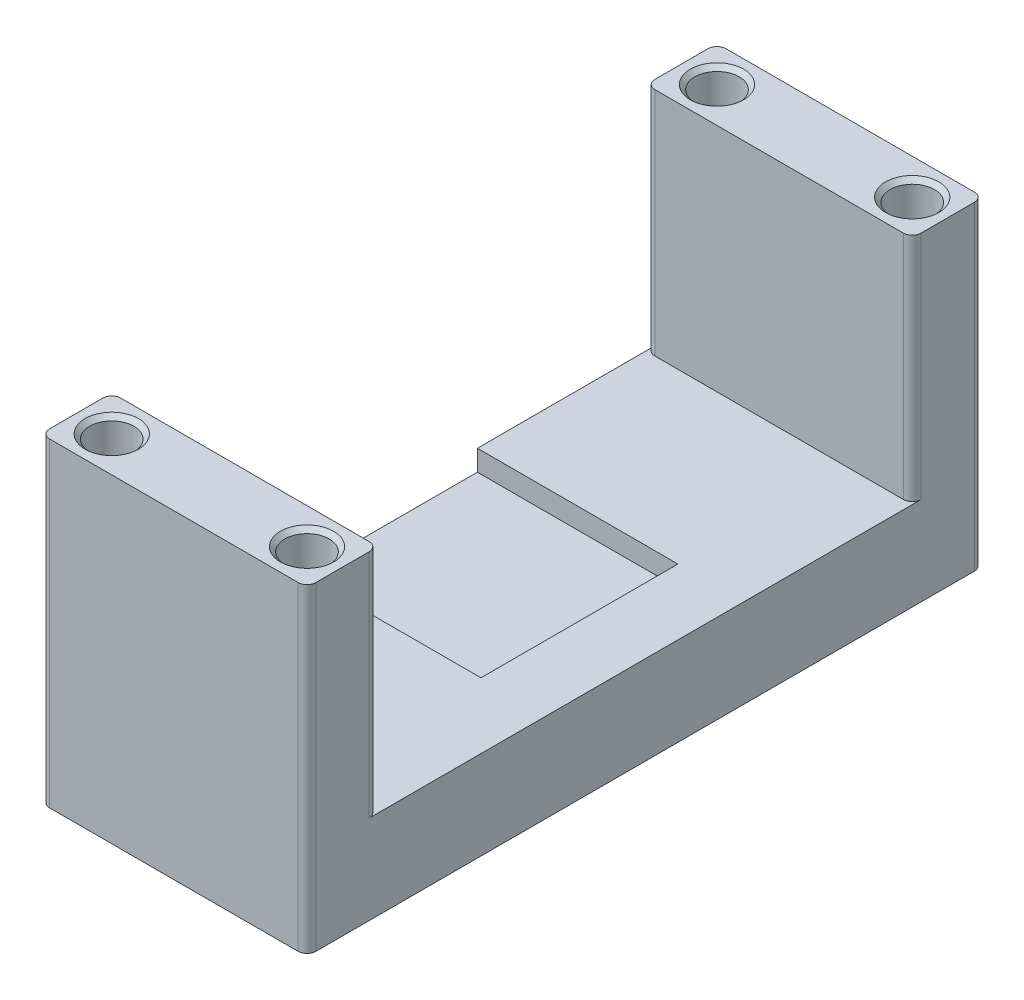
SolidWorks part; units mm, degrees
ref_plane "Front" through (0, 0, 0) normal (0, 0, 1) x (1, 0, 0)
ref_plane "Top" through (0, 0, 0) normal (0, 1, 0) x (1, 0, 0)
ref_plane "Right" through (0, 0, 0) normal (1, 0, 0) x (0, 0, -1)
sketch "Sketch1" plane through (0, 0, 0) normal (0, 1, 0) x (1, 0, 0)
  line L1 (-20.5, 11) -> (7.5, 11) construction
  line L2 (-20.5, 11) -> (-20.5, -11) construction
  line L3 (-20.5, -11) -> (7.5, -11) construction
  line L4 (7.5, 11) -> (7.5, -11) construction
  line L5 (-5.5, 9) -> (5.5, 9) construction
  line L6 (-5.5, 9) -> (-5.5, -9) construction
  line L7 (-5.5, -9) -> (5.5, -9) construction
  line L8 (5.5, 9) -> (5.5, -9) construction
  line L9 (-15, 38.1) -> (15, 38.1)
  line L10 (-15, 38.1) -> (-15, -38.1)
  line L11 (-15, -38.1) -> (15, -38.1)
  line L12 (15, 38.1) -> (15, -38.1)
  point P4 (5.5, 0)
  point P6 (7.5, 0)
  point P11 (0, 9)
  point P17 (0, -38.1)
  point P18 (15, 0)
  dimension "D1" = 22
  dimension "D2" = 28
  dimension "D3" = 7.5
  dimension "D4" = 18
  dimension "D5" = 11
  dimension "D6" = 76.2
  dimension "D7" = 30
extrude "Boss-Extrude1" add sketch "Sketch1" against normal blind 10
sketch "Sketch2" plane through (0, 0, 0) normal (0, 1, 0) x (1, 0, 0)
  line L0 (-15, 38.1) -> (-15, -38.1) construction
  line L1 (-15, 11.1) -> (7.6, 11.1)
  line L2 (-15, 11.1) -> (-15, -11.1)
  line L3 (-15, -11.1) -> (7.6, -11.1)
  line L4 (7.6, 11.1) -> (7.6, -11.1)
  line L5 (7.5, 11) -> (7.5, -11) construction
  point P6 (7.6, 0)
  dimension "D1" = 22.2
  dimension "D2" = 0.1
extrude "Cut-Extrude2" cut sketch "Sketch2" against normal blind 2.335
sketch "Sketch3" plane through (0, 0, 0) normal (0, 1, 0) x (1, 0, 0)
  line L0 (15, 38.1) -> (15, -38.1) construction
  line L1 (-15, 38.1) -> (15, 38.1)
  line L2 (-15, 38.1) -> (-15, 30.1)
  line L3 (-15, 30.1) -> (15, 30.1)
  line L4 (15, 38.1) -> (15, 30.1)
  line L6 (-15, -38.1) -> (15, -38.1)
  line L7 (-15, -38.1) -> (-15, -30.1)
  line L8 (-15, -30.1) -> (15, -30.1)
  line L9 (15, -38.1) -> (15, -30.1)
  dimension "D1" = 8
extrude "Boss-Extrude2" add sketch "Sketch3" along normal blind 26
hole_wizard "Ø5.0mm Dowel Hole1" positions "Sketch4" profile "Sketch6" hole size "Ø5.0" standard "ANSI Metric"
sketch "Sketch4" plane through (0, 26, 0) normal (0, 1, 0) x (1, 0, 0)
  line L0 (-15, 38.1) -> (-15, 30.1) construction
  line L2 (-15, -30.1) -> (-15, -38.1) construction
  line L3 (-15, 38.1) -> (-15, -38.1) construction
  line L4 (15, 38.1) -> (15, -38.1) construction
  point P0 (-11, 34.1)
  point P2 (11, 34.1)
  point P4 (11, -34.1)
  point P6 (-11, -34.1)
  point P12 (-15, 34.1)
  point P20 (-15, -34.1)
  dimension "D1" = 4
  dimension "D2" = 4
sketch "Sketch6" plane through (-11, 26, -34.1) normal (1, 0, 0) x (0, 0, 1)
  line L0 (0, 0) -> (0, 4.6)
  line L1 (0, 4.6) -> (2.5, 4.6)
  line L2 (2.5, 4.6) -> (2.5, 0.5)
  line L3 (2.5, 0.5) -> (3, 0)
  line L5 (3, 0) -> (0, 0)
  line L6 (-2.5, 0.5) -> (-3, 0) construction
  line L10 (0, 4.6) -> (-2.5, 4.6) construction
  line L11 (0, -6.35) -> (0, 107.95) construction
  dimension "Hole Dia." = 5
  dimension "Hole Depth" = 4.6
  dimension "Near C'Sink Dia." = 6
  dimension "Near C'Sink Angle" = 90
  dimension "Drill Angle" = 180
fillet "Fillet1" radius 1 8 edges at (15, 8, -38.1) (15, 13, -30.1) (-15, 13, -30.1) (-15, 8, -38.1) (-15, 13, 30.1) (15, 13, 30.1) (15, 8, 38.1) (-15, 8, 38.1)
equation "\"D1@Cut-Extrude2\"=1.7mm + 0.025in"
